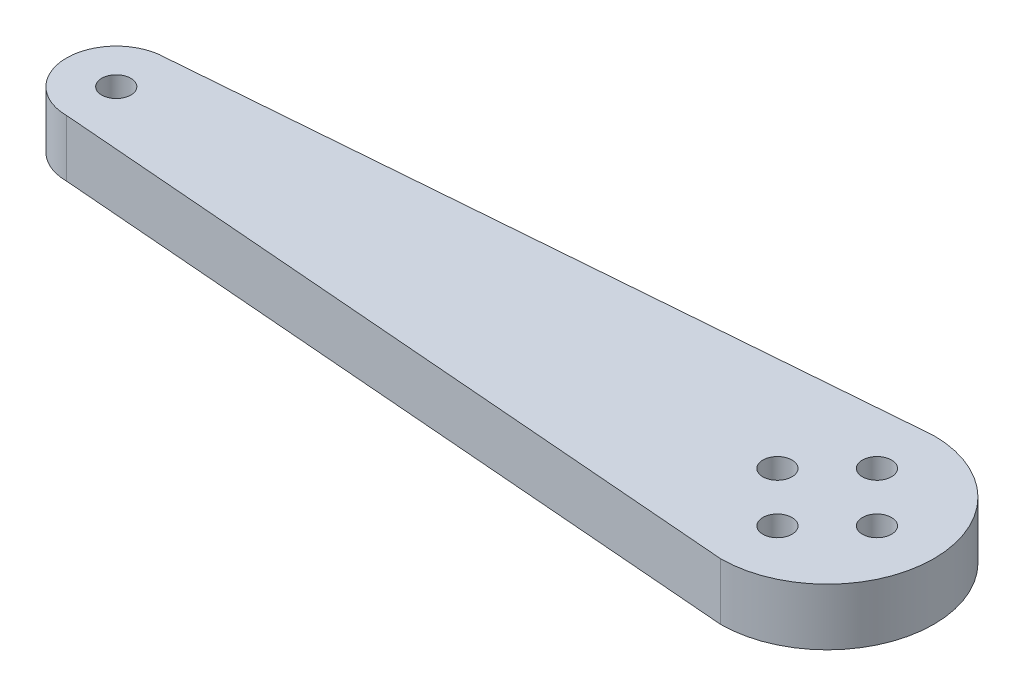
SolidWorks part; units mm, degrees
ref_plane "前视基准面" through (0, 0, 0) normal (0, 0, 1) x (1, 0, 0)
ref_plane "上视基准面" through (0, 0, 0) normal (0, 1, 0) x (1, 0, 0)
ref_plane "右视基准面" through (0, 0, 0) normal (1, 0, 0) x (0, 0, -1)
other "Configuration Table"
sketch "草图1" plane through (0, 0, 0) normal (0, 1, 0) x (1, 0, 0)
  line L1 (100, -15) -> (0, -7)
  line L2 (100, 15) -> (0, 7)
  arc A0 (100, -15) -> (100, 15) centre (100, 0) ccw
  arc A1 (0, 7) -> (0, -7) centre (0, 0) ccw
  circle A2 centre (100, 7) radius 2.05
  circle A3 centre (100, -7) radius 2.05
  circle A4 centre (93, 0) radius 2.05
  circle A5 centre (107, 0) radius 2.05
  circle A6 centre (0, 0) radius 2.05
  dimension "D1" = 14
  dimension "D3" = 14
  dimension "D2" = 7
  dimension "D4" = 7
extrude "凸台-拉伸2" add sketch "草图1" along normal blind 8
